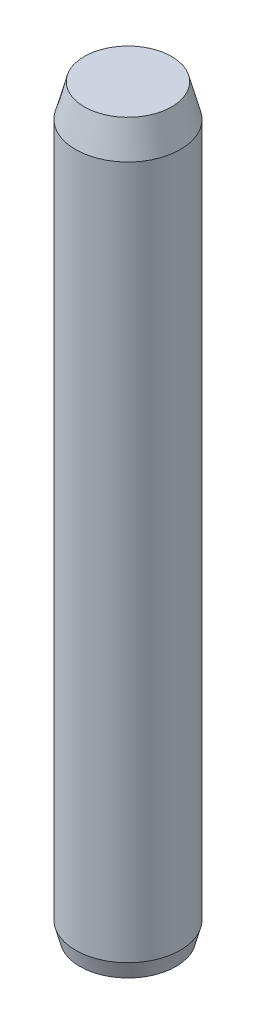
SolidWorks part; units mm, degrees
material "1.7131 (16MnCr5)"
ref_plane "Front Plane" through (0, 0, 0) normal (0, 0, 1) x (1, 0, 0)
ref_plane "Top Plane" through (0, 0, 0) normal (0, 1, 0) x (1, 0, 0)
ref_plane "Right Plane" through (0, 0, 0) normal (1, 0, 0) x (0, 0, -1)
sketch "Sketch1" plane through (0, 0, 0) normal (0, 1, 0) x (1, 0, 0)
  circle A0 centre (0, 0) radius 12
  dimension "D1" = 24
extrude "Boss-Extrude1" add sketch "Sketch1" along normal blind 170
chamfer "Chamfer1" distance 2 angle 75 1 edges at (0, 170, 12)
chamfer "Chamfer2" distance 1 angle 75 1 edges at (0, 0, 12)
